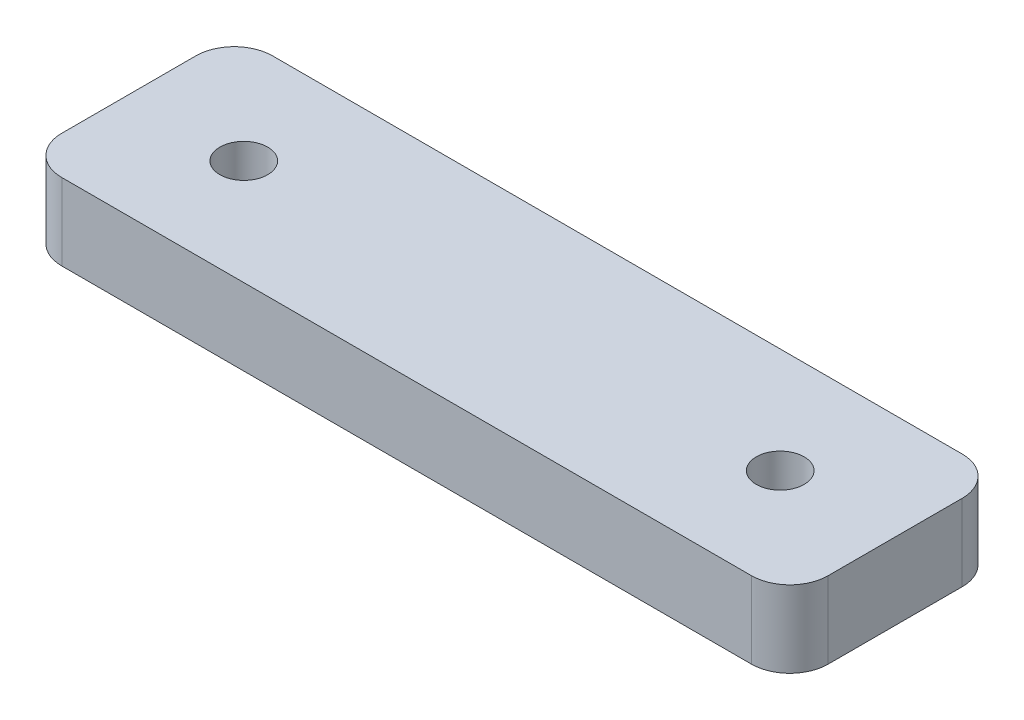
SolidWorks part; units mm, degrees
ref_plane "Front" through (0, 0, 0) normal (0, 0, 1) x (1, 0, 0)
ref_plane "Top" through (0, 0, 0) normal (0, 1, 0) x (1, 0, 0)
ref_plane "Right" through (0, 0, 0) normal (1, 0, 0) x (0, 0, -1)
sketch "Croquis1" plane through (0, 0, 0) normal (0, 1, 0) x (1, 0, 0)
  line L0 (-72.6012, 0) -> (3557.4579, 0) construction
  line L1 (0, -72.6012) -> (0, 3557.4579) construction
  line L3 (-10, -2.75) -> (10, -2.75)
  line L4 (-10, -2.75) -> (-10, 2.75)
  line L5 (-10, 2.75) -> (10, 2.75)
  line L6 (10, -2.75) -> (10, 2.75)
  line L7 (-10, -2.75) -> (10, 2.75) construction
  line L8 (-10, 2.75) -> (10, -2.75) construction
  circle A0 centre (-7, 0) radius 0.625
  circle A1 centre (7, 0) radius 0.625
  point P4 (0, 0)
  dimension "D3" = 1.25
  dimension "D4" = 3
  dimension "D1" = 5.5
  dimension "D2" = 20
extrude "Saliente-Extruir1" add sketch "Croquis1" along normal blind 2
fillet "Redondeo1" radius 1 4 edges at (10, 1, 2.75) (10, 1, -2.75) (-10, 1, -2.75) (-10, 1, 2.75)
